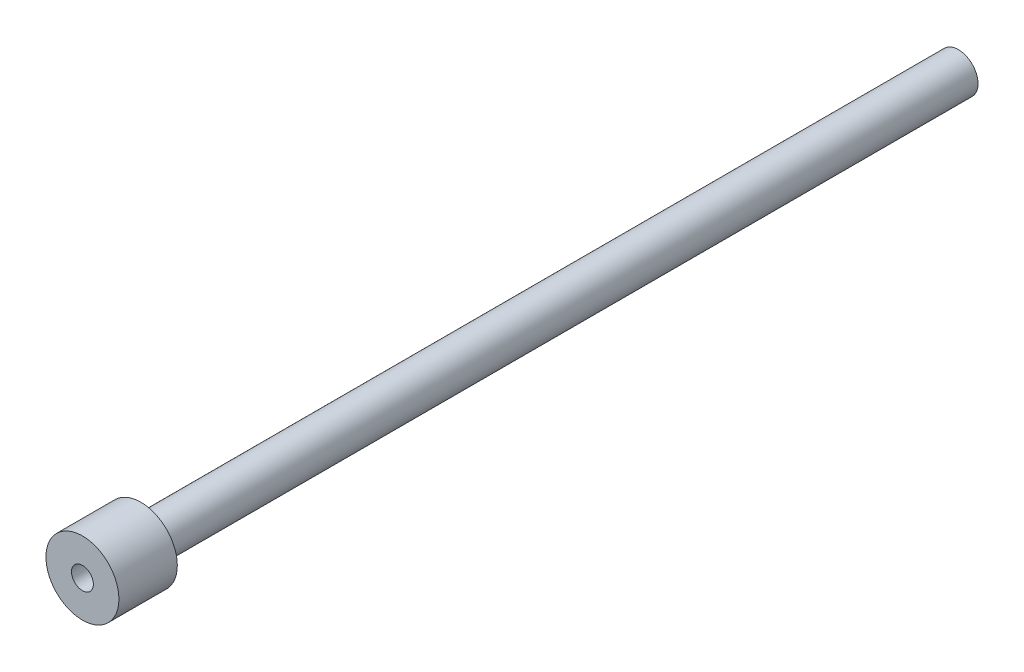
SolidWorks part; units mm, degrees
ref_plane "Front Plane" through (0, 0, 0) normal (0, 0, 1) x (1, 0, 0)
ref_plane "Top Plane" through (0, 0, 0) normal (0, 1, 0) x (1, 0, 0)
ref_plane "Right Plane" through (0, 0, 0) normal (1, 0, 0) x (0, 0, -1)
sketch "Sketch1" plane through (0, 0, 0) normal (0, 0, 1) x (1, 0, 0)
  circle A0 centre (0, 0) radius 12.5
  dimension "D1" = 25
extrude "Boss-Extrude1" add sketch "Sketch1" along normal blind 20
sketch "Sketch2" plane through (0, 0, 0) normal (0, 0, -1) x (-1, 0, 0)
  circle A0 centre (0, 0) radius 10.5
  circle A1 centre (0, 0) radius 6.75
  dimension "D1" = 21
  dimension "D2" = 13.5
extrude "Cut-Extrude1" cut sketch "Sketch2" against normal blind 15
sketch "Sketch3" plane through (0, 0, 20) normal (0, 0, 1) x (1, 0, 0)
  circle A0 centre (0, 0) radius 3.75
  dimension "D1" = 7.5
extrude "Cut-Extrude2" cut sketch "Sketch3" against normal through all
sketch "Sketch4" plane through (0, 0, 0) normal (0, 0, -1) x (-1, 0, 0)
  circle A0 centre (0, 0) radius 3.75 construction
  circle A1 centre (0, 0) radius 6.75
  circle A3 centre (0, 0) radius 3.75
  circle A14 centre (0, 0) radius 6.75
  dimension "D1" = 0
extrude "Boss-Extrude2" add sketch "Sketch4" along normal blind 280
